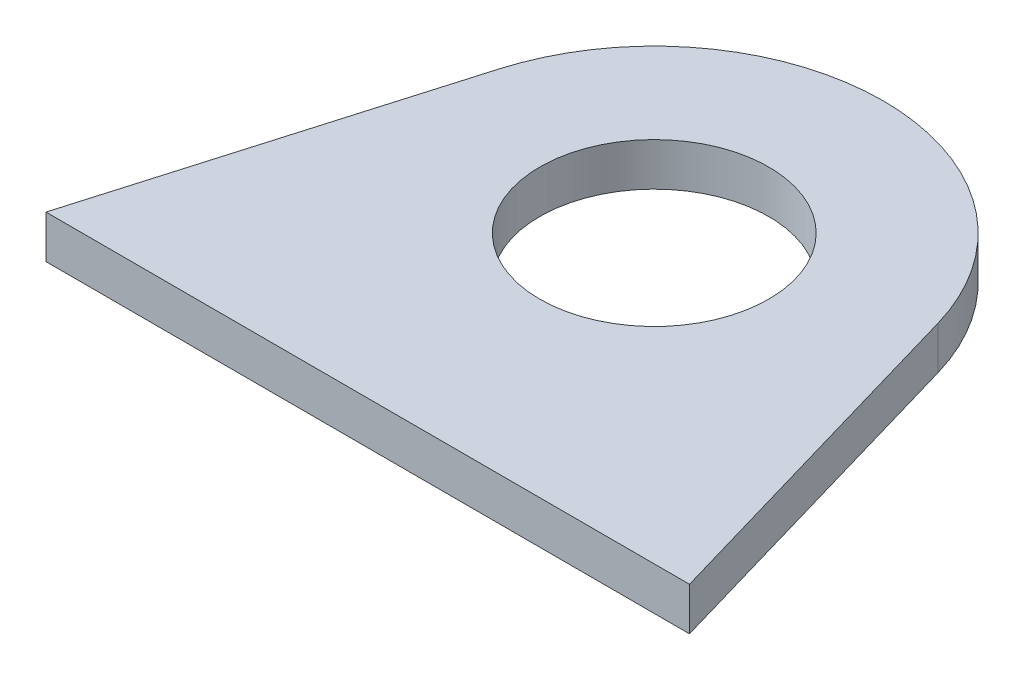
SolidWorks part; units mm, degrees
ref_plane "Front Plane" through (0, 0, 0) normal (0, 0, 1) x (1, 0, 0)
ref_plane "Top Plane" through (0, 0, 0) normal (0, 1, 0) x (1, 0, 0)
ref_plane "Right Plane" through (0, 0, 0) normal (1, 0, 0) x (0, 0, -1)
sketch "Sketch1" plane through (0, 0, 0) normal (0, 1, 0) x (1, 0, 0)
  line L0 (-30.7117, 8.9883) -> (-45.0369, -39.9585)
  line L1 (-45.0369, -39.9585) -> (44.9631, -40.0415)
  line L2 (44.9631, -40.0415) -> (30.7282, 8.9317)
  circle A0 centre (0, 0) radius 16
  arc A1 (30.7282, 8.9317) -> (-30.7117, 8.9883) centre (0, 0) ccw
  point P8 (-45.0369, -40.0415)
  dimension "D1" = 32
  dimension "D2" = 40
  dimension "D3" = 16
  dimension "D4" = 90
extrude "Boss-Extrude1" add sketch "Sketch1" along normal blind 6
